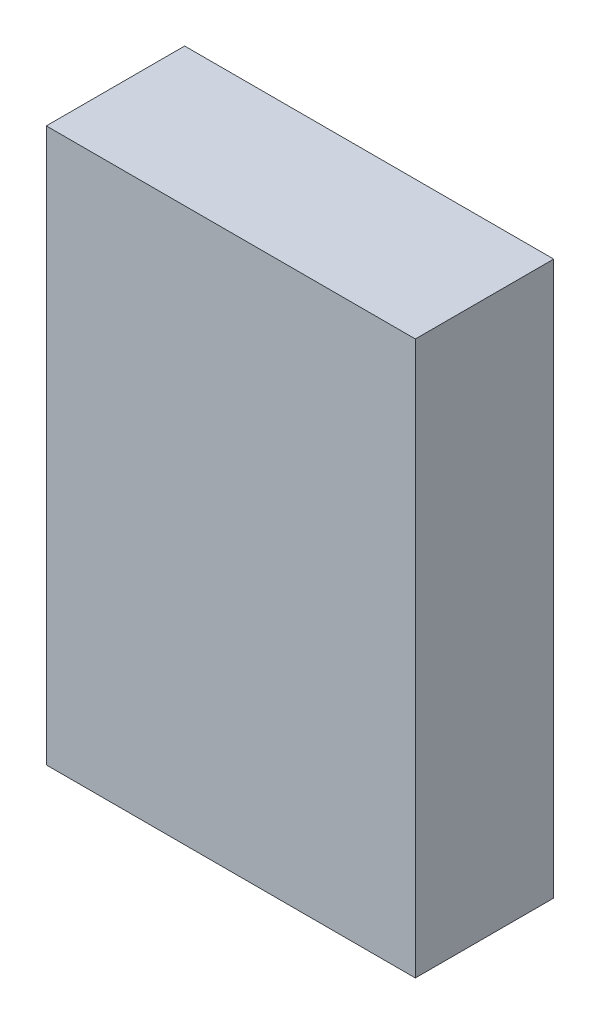
SolidWorks part; units mm, degrees
ref_plane "정면" through (0, 0, 0) normal (0, 0, 1) x (1, 0, 0)
ref_plane "윗면" through (0, 0, 0) normal (0, 1, 0) x (1, 0, 0)
ref_plane "우측면" through (0, 0, 0) normal (1, 0, 0) x (0, 0, -1)
sketch "스케치1" plane through (0, 0, 0) normal (0, 1, 0) x (1, 0, 0)
  line L1 (-609.5, 228.5) -> (609.5, 228.5)
  line L2 (-609.5, 228.5) -> (-609.5, -228.5)
  line L3 (-609.5, -228.5) -> (609.5, -228.5)
  line L4 (609.5, 228.5) -> (609.5, -228.5)
  line L5 (-609.5, 228.5) -> (609.5, -228.5) construction
  line L6 (-609.5, -228.5) -> (609.5, 228.5) construction
  point P0 (0, 0)
  dimension "D1" = 1219
  dimension "D2" = 457
extrude "보스-돌출1" add sketch "스케치1" along normal blind 1828
